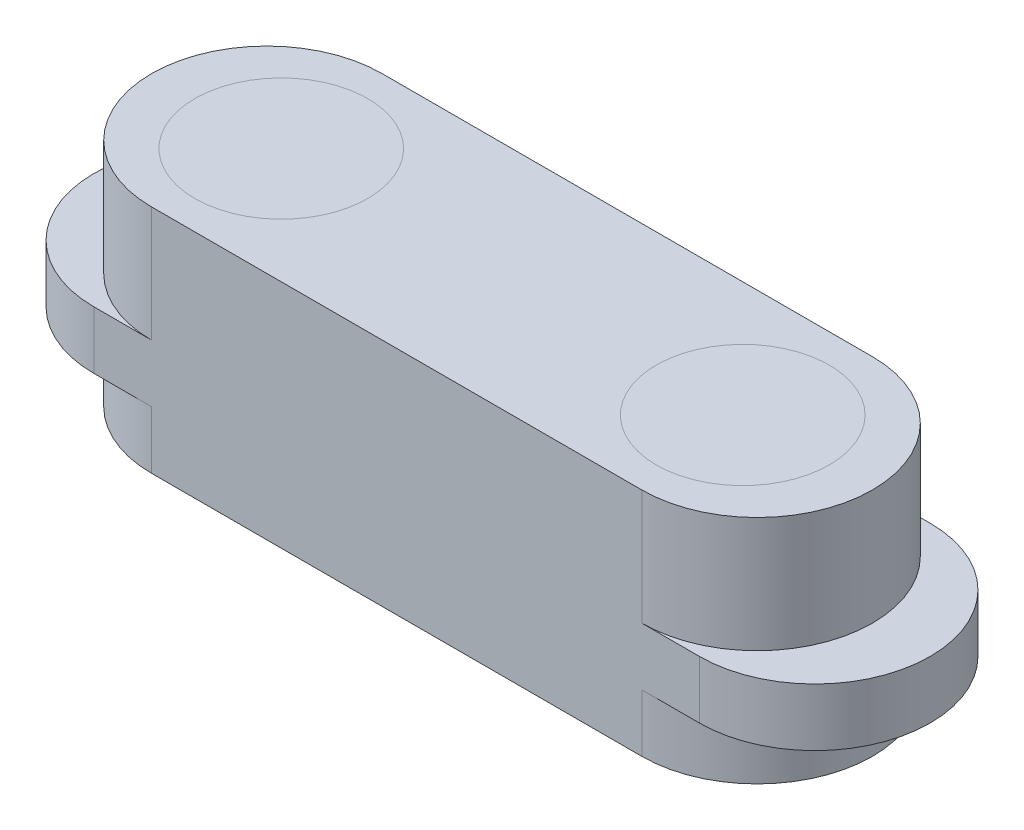
SolidWorks part; units mm, degrees
ref_plane "Front Plane" through (0, 0, 0) normal (0, 0, 1) x (1, 0, 0)
ref_plane "Top Plane" through (0, 0, 0) normal (0, 1, 0) x (1, 0, 0)
ref_plane "Right Plane" through (0, 0, 0) normal (1, 0, 0) x (0, 0, -1)
sketch "Sketch4" plane through (0, 0, 0) normal (0, 1, 0) x (1, 0, 0)
  line L0 (0, 0) -> (10.5, 0) construction
  line L1 (0, 2) -> (10.5, 2)
  line L2 (0, -2) -> (10.5, -2)
  arc A0 (0, 2) -> (0, -2) centre (0, 0) ccw
  arc A1 (10.5, -2) -> (10.5, 2) centre (10.5, 0) ccw
  point P3 (5.25, 0)
  point P8 (-2, 0)
  point P9 (12.5, 0)
  dimension "D1" = 14.5
  dimension "D2" = 4
extrude "Boss-Extrude2" add sketch "Sketch4" along normal blind 1
sketch "Sketch5" plane through (0, 1, 0) normal (0, 1, 0) x (1, 0, 0)
  line L0 (1, 0) -> (9.5, 0) construction
  line L1 (1, 2) -> (9.5, 2)
  line L2 (1, -2) -> (9.5, -2)
  arc A0 (1, 2) -> (1, -2) centre (1, 0) ccw
  arc A1 (9.5, -2) -> (9.5, 2) centre (9.5, 0) ccw
  point P2 (5.25, 0)
  point P7 (-1, 0)
  point P8 (11.5, 0)
  dimension "D1" = 12.5
  dimension "D2" = 4
  dimension "D3" = 1
  dimension "D4" = 0
extrude "Boss-Extrude3" add sketch "Sketch5" along normal blind 2
sketch "Sketch7" plane through (0, 3, 0) normal (0, 1, 0) x (1, 0, 0)
  circle A0 centre (1.25, 0) radius 1.5
  circle A1 centre (9.25, 0) radius 1.5
  circle A2 centre (4, 0) radius 0.45
  circle A3 centre (6.5, 0) radius 0.45
  dimension "D1" = 3
  dimension "D2" = 3
  dimension "D10" = 0.9
  dimension "D11" = 0.9
  dimension "D3" = 1.25
  dimension "D4" = 0
  dimension "D5" = 8
  dimension "D6" = 0
  dimension "D7" = 0
  dimension "D8" = 0
  dimension "D9" = 2.5
  dimension "D12" = 2.75
extrude "Cut-Extrude1" cut sketch "Sketch7" against normal blind 1
sketch "Sketch8" plane through (0, 2, 0) normal (0, 1, 0) x (1, 0, 0)
  circle A0 centre (1.25, 0) radius 1.5
  circle A1 centre (1.25, 0) radius 1.5 construction
  circle A2 centre (9.25, 0) radius 1.5
  circle A3 centre (9.25, 0) radius 1.5 construction
  dimension "D1" = 0
  dimension "D2" = 0
extrude "Boss-Extrude4" add sketch "Sketch8" along normal up to surface (1 mm away) separate body up to face at (1.25, 3, 1.5)
sketch "Sketch9" plane through (0, 2, 0) normal (0, 1, 0) x (1, 0, 0)
  circle A0 centre (4, 0) radius 0.45
  circle A1 centre (6.5, 0) radius 0.45
  circle A2 centre (4, 0) radius 0.45 construction
  circle A3 centre (6.5, 0) radius 0.45 construction
  dimension "D1" = 0
  dimension "D2" = 0
extrude "Boss-Extrude12" add sketch "Sketch9" along normal blind 1 and the other way offset from surface (4.5 mm away) 2.5 separate body other way up to face at (5.25, 0, 0)
sketch "Sketch11" plane through (0, 0, 0) normal (0, -1, 0) x (1, 0, 0)
  line L0 (1, 2) -> (9.5, 2)
  line L1 (0, 2) -> (10.5, 2) construction
  line L2 (9.5, -2) -> (1, -2)
  arc A0 (1, 2) -> (1, -2) centre (1, 0) ccw construction
  arc A1 (1, -2) -> (1, 2) centre (1, 0) cw
  arc A2 (9.5, 2) -> (9.5, -2) centre (9.5, 0) cw
extrude "Boss-Extrude13" add sketch "Sketch11" along normal blind 1
